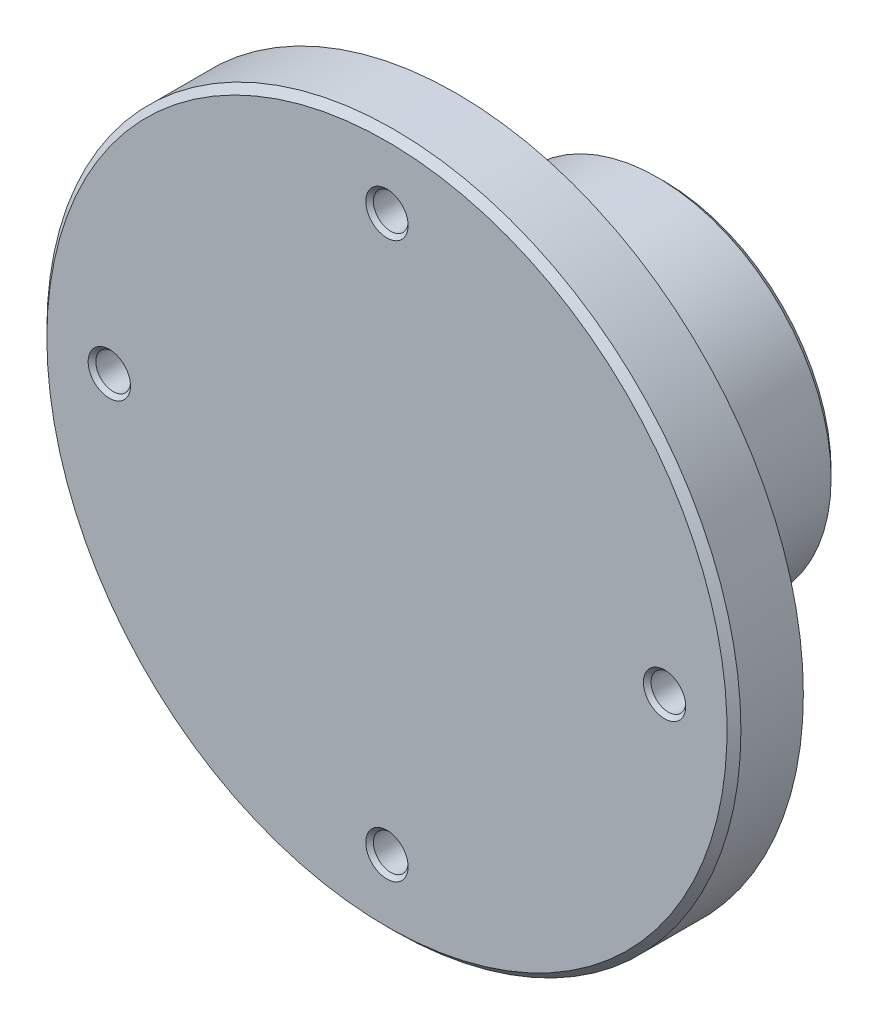
SolidWorks part; units mm, degrees
material "6061 合金"
ref_plane "前视基准面" through (0, 0, 0) normal (0, 0, 1) x (1, 0, 0)
ref_plane "上视基准面" through (0, 0, 0) normal (0, 1, 0) x (1, 0, 0)
ref_plane "右视基准面" through (0, 0, 0) normal (1, 0, 0) x (0, 0, -1)
sketch "草图1" plane through (0, 0, 0) normal (1, 0, 0) x (0, 0, -1)
  line L0 (-109.8592, 0) -> (265.3521, 0) construction
  line L1 (0, 0) -> (0, 25)
  line L2 (0, 25) -> (5, 25)
  line L3 (5, 25) -> (5, 12.5)
  line L4 (5, 12.5) -> (20, 12.5)
  line L5 (20, 12.5) -> (20, 0)
  line L6 (0, 0) -> (20, 0)
  dimension "D1" = 25
  dimension "D2" = 50
  dimension "D3" = 15
  dimension "D4" = 5
revolve "旋转1" add sketch "草图1" angle 360 about L0
hole_wizard "M10 螺纹孔1" positions "3D草图1" profile "草图2" tap size "M10" standard "GB"
sketch3d "3D草图1"
  line L0 (0, 0, -20) -> (0, 0, -5) construction
  point P0 (0, 0, -20)
sketch "草图2" plane through (0, 0, -20) normal (1, 0, 0) x (0, 1, 0)
  line L0 (0, 0) -> (0, 14.5537)
  line L1 (0, 14.5537) -> (4.25, 12)
  line L2 (4.25, 12) -> (4.25, 0.775)
  line L3 (4.25, 0.775) -> (5.025, 0)
  line L5 (5.025, 0) -> (0, 0)
  line L6 (-4.25, 0.775) -> (-5.025, 0) construction
  line L10 (0, 14.5537) -> (-4.25, 12) construction
  line L11 (0, -6.35) -> (0, 107.95) construction
  dimension "螺纹孔钻头直径" = 8.5
  dimension "螺纹孔钻头深度" = 12
  dimension "近端锥形沉头孔直径" = 10.05
  dimension "近端锥形沉头孔角度" = 90
  dimension "导头角度" = 118
cosmetic thread "孔螺蚊线1" parameters "D1"=12, "D2"=10
chamfer "倒角1" distance 3 angle 45 1 edges at (12.5, 0, -5)
sketch "草图3" plane through (0, 0, -5) normal (0, 0, -1) x (-1, 0, 0)
  circle A0 centre (0, 0) radius 20 construction
  point P3 (0, 20)
  point P4 (-20, 0)
  point P5 (20, 0)
  point P6 (0, -20)
  dimension "D1" = 40
hole_wizard "M3 螺纹孔1" positions "草图4" profile "草图5" tap size "M3" standard "GB"
sketch "草图4" plane through (0, 0, 0) normal (0, 0, 1) x (1, 0, 0)
  point P0 (-20, 0)
  point P3 (0, 20)
  point P6 (20, 0)
  point P9 (0, -20)
sketch "草图5" plane through (-20, 0, 0) normal (1, 0, 0) x (0, -1, 0)
  line L0 (0, 0) -> (0, 8.2511)
  line L1 (0, 8.2511) -> (1.25, 7.5)
  line L2 (1.25, 7.5) -> (1.25, 0.275)
  line L3 (1.25, 0.275) -> (1.525, 0)
  line L5 (1.525, 0) -> (0, 0)
  line L6 (-1.25, 0.275) -> (-1.525, 0) construction
  line L10 (0, 8.2511) -> (-1.25, 7.5) construction
  line L11 (0, -6.35) -> (0, 107.95) construction
  dimension "螺纹孔钻头直径" = 2.5
  dimension "螺纹孔钻头深度" = 7.5
  dimension "近端锥形沉头孔直径" = 3.05
  dimension "近端锥形沉头孔角度" = 90
  dimension "导头角度" = 118
cosmetic thread "孔螺蚊线2" parameters "D1"=5, "D2"=3
cosmetic thread "孔螺蚊线3" parameters "D1"=5, "D2"=3
cosmetic thread "孔螺蚊线4" parameters "D1"=5, "D2"=3
cosmetic thread "孔螺蚊线5" parameters "D1"=5, "D2"=3
chamfer "倒角2" distance 0.5 angle 45 2 edges at (25, 0, 0) (12.5, 0, -20)
